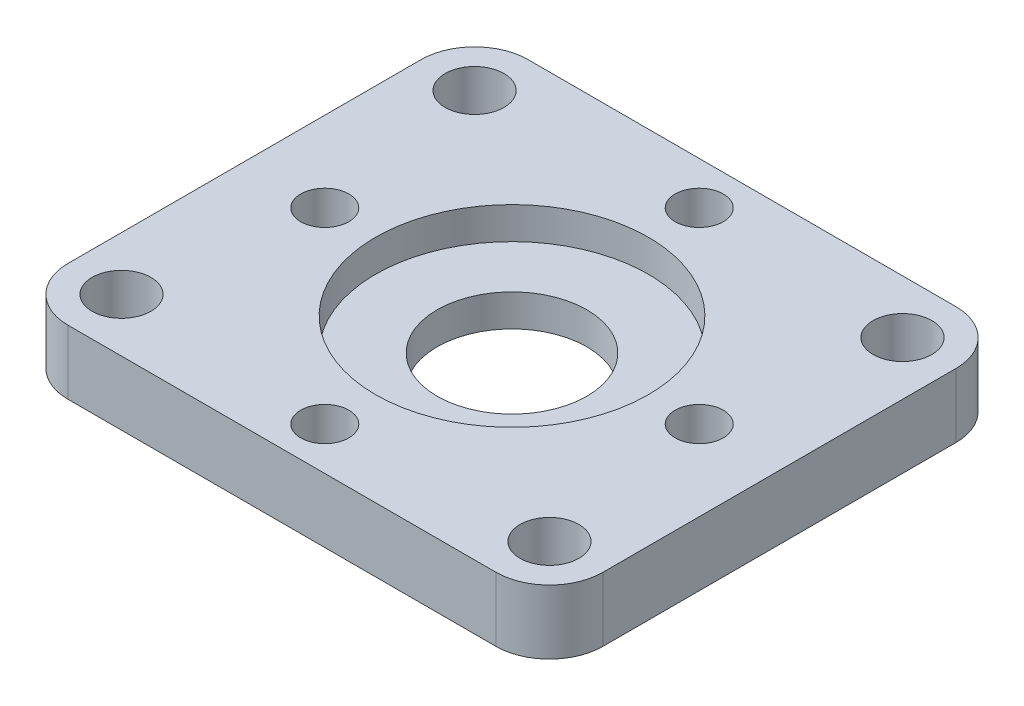
SolidWorks part; units mm, degrees
ref_plane "Front Plane" through (0, 0, 0) normal (0, 0, 1) x (1, 0, 0)
ref_plane "Top Plane" through (0, 0, 0) normal (0, 1, 0) x (1, 0, 0)
ref_plane "Right Plane" through (0, 0, 0) normal (1, 0, 0) x (0, 0, -1)
sketch "Sketch1" plane through (0, 0, 0) normal (0, 1, 0) x (1, 0, 0)
  line L1 (-20, -16.5) -> (20, -16.5)
  line L2 (-20, -16.5) -> (-20, 16.5)
  line L3 (-20, 16.5) -> (20, 16.5)
  line L4 (20, -16.5) -> (20, 16.5)
  line L5 (-20, -16.5) -> (20, 16.5) construction
  line L6 (-20, 16.5) -> (20, -16.5) construction
  line L7 (25, -21.5) -> (-25, -21.5)
  line L8 (25, -21.5) -> (25, 21.5)
  line L9 (25, 21.5) -> (-25, 21.5)
  line L10 (-25, -21.5) -> (-25, 21.5)
  line L11 (25, -21.5) -> (-25, 21.5) construction
  line L12 (25, 21.5) -> (-25, -21.5) construction
  circle A0 centre (-20, 16.5) radius 2.75
  circle A1 centre (20, 16.5) radius 2.75
  circle A2 centre (-20, -16.5) radius 2.75
  circle A3 centre (20, -16.5) radius 2.75
  point P0 (0, 0)
  point P10 (0, 0)
  dimension "D3" = 5
  dimension "D1" = 40
  dimension "D2" = 33
  dimension "D4" = 5
extrude "Boss-Extrude1" add sketch "Sketch1" along normal blind 6 contours L10 L7 L8 L9 A3 L1 A2 L2 A0 L3 A1 L4 | A3 L4 A1 L3 A0 L2 A2 L1
sketch "Sketch2" plane through (0, 6, 0) normal (0, 1, 0) x (1, 0, 0)
  circle A0 centre (0, 0) radius 7
extrude "Cut-Extrude1" cut sketch "Sketch2" against normal blind 6
sketch "Sketch3" plane through (0, 6, 0) normal (0, 1, 0) x (1, 0, 0)
  circle A0 centre (0, 0) radius 17.5
  circle A1 centre (0, 17.5) radius 2.25
  circle A2 centre (17.5, 0) radius 2.25
  circle A3 centre (0, -17.5) radius 2.25
  circle A4 centre (-17.5, 0) radius 2.25
extrude "Cut-Extrude2" cut sketch "Sketch3" against normal blind 6 contours A0 A1 | A0 A1 | A0 A2 | A0 A2 | A0 A4 | A0 A4 | A0 A3 | A0 A3
sketch "Sketch4" plane through (0, 6, 0) normal (0, 1, 0) x (1, 0, 0)
  circle A0 centre (0, 0) radius 12.75
extrude "Cut-Extrude3" cut sketch "Sketch4" against normal blind 3
fillet "Fillet1" radius 5 4 edges at (-25, 3, 21.5) (25, 3, 21.5) (25, 3, -21.5) (-25, 3, -21.5)
sketch "Sketch5" plane through (0, 6, 0) normal (0, 1, 0) x (1, 0, 0)
  circle A0 centre (0, 0) radius 25.9278
